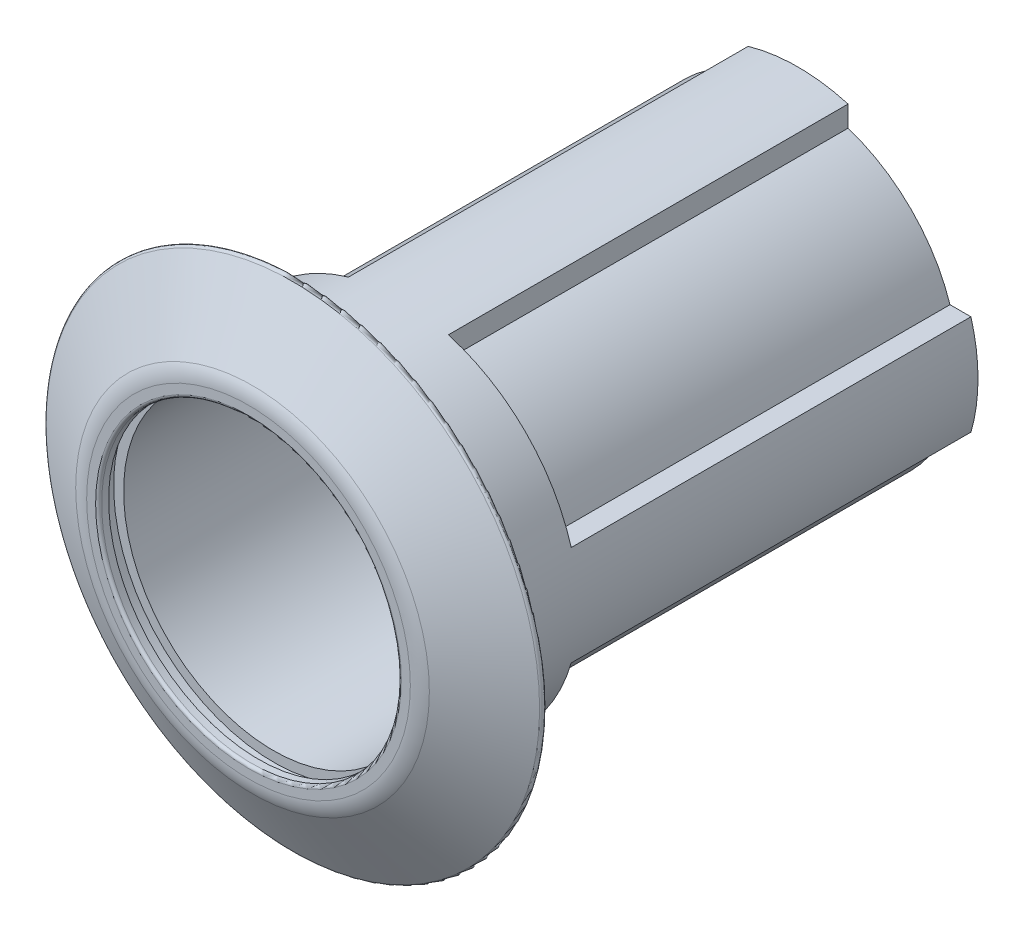
SolidWorks part; units mm, degrees
ref_plane "前视基准面" through (0, 0, 0) normal (0, 0, 1) x (1, 0, 0)
ref_plane "上视基准面" through (0, 0, 0) normal (0, 1, 0) x (1, 0, 0)
ref_plane "右视基准面" through (0, 0, 0) normal (1, 0, 0) x (0, 0, -1)
sketch "草图1" plane through (0, 0, 0) normal (1, 0, 0) x (0, 0, -1)
  line L0 (-31.8443, 0) -> (77.7049, 0) construction
  line L1 (0, 15.3) -> (0, 16.1962)
  line L2 (0.4019, 17.6962) -> (4.4402, 24.6906)
  line L3 (5, 24.5406) -> (5, 18)
  line L4 (5, 18) -> (55, 18)
  line L5 (55, 18) -> (55, 15)
  line L6 (55, 15) -> (2.5, 15)
  line L7 (2.5, 15) -> (2.5, 16)
  line L8 (2.5, 16) -> (1, 16)
  line L9 (1, 16) -> (1, 15)
  line L10 (1, 15) -> (0.3, 15)
  arc A0 (0, 16.1962) -> (0.4019, 17.6962) centre (3, 16.1962) cw
  arc A1 (4.4402, 24.6906) -> (5, 24.5406) centre (4.7, 24.5406) cw
  arc A2 (0, 15.3) -> (0.3, 15) centre (0.3, 15.3) ccw
  point P15 (0, 17)
  point P20 (0, 15)
  dimension "D10" = 3
  dimension "D11" = 0.3
  dimension "D1" = 55
  dimension "D2" = 1.5
  dimension "D3" = 1
  dimension "D4" = 15
  dimension "D5" = 1
  dimension "D6" = 50
  dimension "D7" = 30
  dimension "D8" = 2
  dimension "D9" = 18
revolve "旋转1" add sketch "草图1" angle 360 about L0
sketch "草图2" plane through (0, 0, -55) normal (0, 0, -1) x (-1, 0, 0)
  line L2 (-5, 17.2916) -> (-5, 15.1987)
  line L3 (5, 17.2916) -> (5, 15.1987)
  line L4 (-17.2916, -5) -> (-15.1987, -5)
  line L5 (-17.2916, 5) -> (-15.1987, 5)
  line L12 (15.1987, 5) -> (17.2916, 5)
  line L14 (15.1987, -5) -> (17.2916, -5)
  line L15 (5, -15.1987) -> (5, -17.2916)
  line L16 (-5, -15.1987) -> (-5, -17.2916)
  arc A0 (-15.1987, -5) -> (-5, -15.1987) centre (0, 0) ccw
  circle A1 centre (0, 0) radius 18 construction
  arc A2 (-17.2916, -5) -> (-5, -17.2916) centre (0, 0) ccw
  arc A3 (5, -17.2916) -> (17.2916, -5) centre (0, 0) ccw
  arc A4 (5, -15.1987) -> (15.1987, -5) centre (0, 0) ccw
  arc A5 (17.2916, 5) -> (5, 17.2916) centre (0, 0) ccw
  arc A6 (15.1987, 5) -> (5, 15.1987) centre (0, 0) ccw
  arc A7 (-5, 17.2916) -> (-17.2916, 5) centre (0, 0) ccw
  arc A8 (-5, 15.1987) -> (-15.1987, 5) centre (0, 0) ccw
  dimension "D1" = 32
extrude "切除-拉伸1" cut sketch "草图2" against normal blind 40
